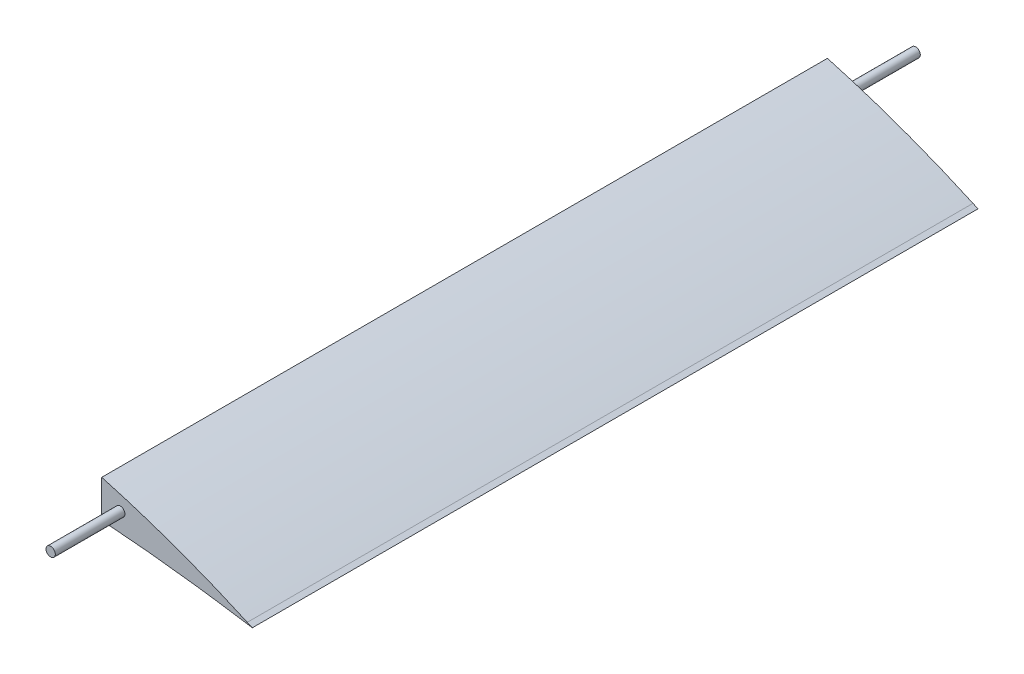
SolidWorks part; units mm, degrees
ref_plane "Front Plane" through (0, 0, 0) normal (0, 0, 1) x (1, 0, 0)
ref_plane "Top Plane" through (0, 0, 0) normal (0, 1, 0) x (1, 0, 0)
ref_plane "Right Plane" through (0, 0, 0) normal (1, 0, 0) x (0, 0, -1)
curve "Curve1"
  spline degree 3 poles (250.0905, 0.3018, 0) (249.9672, 0.3575, 0) (249.4747, 0.5802, 0) (248.3688, 1.0775, 0) (246.5311, 1.8956, 0) (243.97, 3.0187, 0) (240.6975, 4.4253, 0) (236.7287, 6.0881, 0) (232.0832, 7.9766, 0) (226.7833, 10.0544, 0) (220.8563, 12.2845, 0) (214.3322, 14.6254, 0) (207.2459, 17.0358, 0) (199.6354, 19.4726, 0) (191.5431, 21.8941, 0) (183.0146, 24.2576, 0) (174.0994, 26.5236, 0) (164.8497, 28.6528, 0) (155.3218, 30.6102, 0) (145.574, 32.3628, 0) (135.6679, 33.8811, 0) (125.6669, 35.1398, 0) (115.6368, 36.1207, 0) (105.5943, 36.804, 0) (95.5386, 37.2049, 0) (85.5334, 37.0417, 0) (75.7163, 36.3461, 0) (66.2328, 35.1462, 0) (57.1612, 33.4871, 0) (48.5745, 31.4248, 0) (40.5395, 29.0235, 0) (33.1158, 26.3532, 0) (26.3548, 23.4892, 0) (20.2996, 20.5079, 0) (14.9856, 17.4843, 0) (10.439, 14.4912, 0) (6.678, 11.5948, 0) (3.7114, 8.8542, 0) (1.5382, 6.3121, 0) (0.1509, 3.9928, 0) (-0.4561, 1.8641, 0) (-0.1455, -0.0657, 0) (1.0874, -1.5729, 0) (3.0441, -2.5516, 0) (5.6254, -3.1273, 0) (8.8498, -3.3551, 0) (12.7046, -3.2653, 0) (17.1664, -2.8882, 0) (22.2028, -2.2588, 0) (27.778, -1.4179, 0) (33.8542, -0.4079, 0) (40.3935, 0.7222, 0) (47.3585, 1.9245, 0) (54.7128, 3.1486, 0) (62.4221, 4.3431, 0) (70.4528, 5.4592, 0) (78.7727, 6.4469, 0) (87.3496, 7.2603, 0) (96.2165, 7.8657, 0) (105.3847, 8.1961, 0) (114.7995, 8.4827, 0) (124.348, 8.6738, 0) (133.9251, 8.7623, 0) (143.476, 8.7363, 0) (152.944, 8.5908, 0) (162.2721, 8.3266, 0) (171.4027, 7.9474, 0) (180.2781, 7.4625, 0) (188.8414, 6.8852, 0) (197.0363, 6.2309, 0) (204.8083, 5.5194, 0) (212.1048, 4.7711, 0) (218.8756, 4.0084, 0) (225.0732, 3.2526, 0) (230.6536, 2.5267, 0) (235.5766, 1.8504, 0) (239.8062, 1.2436, 0) (243.3111, 0.7223, 0) (246.0651, 0.3016, 0) (248.0475, -0.007, 0) (249.243, -0.1956, 0) (249.776, -0.2805, 0) (249.9095, -0.3018, 0) knots 0 0 0 0 0.00078 0.003116 0.006991 0.012379 0.01924 0.027529 0.037189 0.048153 0.06035 0.0737 0.088116 0.103505 0.119772 0.136815 0.154529 0.172806 0.191536 0.210607 0.229904 0.249313 0.268718 0.288003 0.307345 0.326725 0.345665 0.364063 0.381812 0.398811 0.414954 0.430141 0.444276 0.457267 0.469034 0.479505 0.488628 0.496375 0.502755 0.507847 0.511864 0.515267 0.518668 0.522659 0.527659 0.533842 0.541252 0.549872 0.559649 0.570512 0.582379 0.595163 0.608775 0.623132 0.63815 0.653755 0.669877 0.686453 0.703425 0.721111 0.739346 0.757734 0.776176 0.794567 0.812801 0.830771 0.84837 0.865489 0.88202 0.897855 0.912888 0.927018 0.940145 0.952174 0.963016 0.972591 0.980825 0.987653 0.993022 0.996888 0.999221 1 1 1 1
sketch "Sketch1" plane through (0, 0, 0) normal (0, 0, 1) x (1, 0, 0)
  line L0 (250.0905, 0.3018) -> (252.2491, -0.6745)
  line L2 (187.4095, 23.0316) -> (187.4095, 6.9716)
  line L5 (249.9095, -0.3018) -> (252.2491, -0.6745)
  spline S0 degree 3 poles (2456.644, 4483.8801) (345.0905, -56.1566) (299.6173, -21.964) (248.3688, 1.0775) (246.5311, 1.8956) (243.97, 3.0187) (240.6975, 4.4253) (236.7287, 6.0881) (232.0832, 7.9766) (226.7833, 10.0544) (220.8563, 12.2845) (214.3322, 14.6254) (207.2459, 17.0358) (199.6354, 19.4726) (191.5431, 21.8941) (183.0146, 24.2576) (174.0994, 26.5236) (164.8497, 28.6528) (155.3218, 30.6102) (145.574, 32.3628) (135.6679, 33.8811) (125.6669, 35.1398) (115.6368, 36.1207) (105.5943, 36.804) (95.5386, 37.2049) (85.5334, 37.0417) (75.7163, 36.3461) (66.2328, 35.1462) (57.1612, 33.4871) (48.5745, 31.4248) (40.5395, 29.0235) (33.1158, 26.3532) (26.3548, 23.4892) (20.2996, 20.5079) (14.9856, 17.4843) (10.439, 14.4912) (6.678, 11.5948) (3.7114, 8.8542) (1.5382, 6.3121) (0.1509, 3.9928) (-0.4561, 1.8641) (-0.1455, -0.0657) (1.0874, -1.5729) (3.0441, -2.5516) (5.6254, -3.1273) (8.8498, -3.3551) (12.7046, -3.2653) (17.1664, -2.8882) (22.2028, -2.2588) (27.778, -1.4179) (33.8542, -0.4079) (40.3935, 0.7222) (47.3585, 1.9245) (54.7128, 3.1486) (62.4221, 4.3431) (70.4528, 5.4592) (78.7727, 6.4469) (87.3496, 7.2603) (96.2165, 7.8657) (105.3847, 8.1961) (114.7995, 8.4827) (124.348, 8.6738) (133.9251, 8.7623) (143.476, 8.7363) (152.944, 8.5908) (162.2721, 8.3266) (171.4027, 7.9474) (180.2781, 7.4625) (188.8414, 6.8852) (197.0363, 6.2309) (204.8083, 5.5194) (212.1048, 4.7711) (218.8756, 4.0084) (225.0732, 3.2526) (230.6536, 2.5267) (235.5766, 1.8504) (239.8062, 1.2436) (243.3111, 0.7223) (246.0651, 0.3016) (248.0475, -0.007) (310.4513, -9.8504) (370.4532, -30.5336) (1217.1202, 4900.8972) knots -0.316987 -0.316987 -0.316987 -0.316987 0.00078 0.003116 0.006991 0.012379 0.01924 0.027529 0.037189 0.048153 0.06035 0.0737 0.088116 0.103505 0.119772 0.136815 0.154529 0.172806 0.191536 0.210607 0.229904 0.249313 0.268718 0.288003 0.307345 0.326725 0.345665 0.364063 0.381812 0.398811 0.414954 0.430141 0.444276 0.457267 0.469034 0.479505 0.488628 0.496375 0.502755 0.507847 0.511864 0.515267 0.518668 0.522659 0.527659 0.533842 0.541252 0.549872 0.559649 0.570512 0.582379 0.595163 0.608775 0.623132 0.63815 0.653755 0.669877 0.686453 0.703425 0.721111 0.739346 0.757734 0.776176 0.794567 0.812801 0.830771 0.84837 0.865489 0.88202 0.897855 0.912888 0.927018 0.940145 0.952174 0.963016 0.972591 0.980825 0.987653 0.993022 0.996888 0.999221 1.357276 1.357276 1.357276 1.357276 only from (250.0905, 0.3018) to (249.9095, -0.3018) construction
  spline S1 degree 3 poles (250.0905, 0.3018) (249.9672, 0.3575) (249.4747, 0.5802) (248.3688, 1.0775) (246.5311, 1.8956) (243.97, 3.0187) (240.6975, 4.4253) (236.7287, 6.0881) (232.0832, 7.9766) (226.7833, 10.0544) (220.8563, 12.2845) (214.3322, 14.6254) (207.2459, 17.0358) (199.6354, 19.4726) (192.963, 21.4692) (188.8298, 22.638) (187.4095, 23.0316) knots 0 0 0 0 0.00078 0.003116 0.006991 0.012379 0.01924 0.027529 0.037189 0.048153 0.06035 0.0737 0.088116 0.103505 0.119772 0.12827 0.12827 0.12827 0.12827
  spline S2 degree 3 poles (187.4095, 6.9716) (187.9265, 6.9347) (191.1827, 6.6982) (197.0363, 6.2309) (204.8083, 5.5194) (212.1048, 4.7711) (218.8756, 4.0084) (225.0732, 3.2526) (230.6536, 2.5267) (235.5766, 1.8504) (239.8062, 1.2436) (243.3111, 0.7223) (246.0651, 0.3016) (248.0475, -0.007) (249.243, -0.1956) (249.776, -0.2805) (249.9095, -0.3018) knots 0.879031 0.879031 0.879031 0.879031 0.88202 0.897855 0.912888 0.927018 0.940145 0.952174 0.963016 0.972591 0.980825 0.987653 0.993022 0.996888 0.999221 1 1 1 1
  dimension "D1" = 187.4095
extrude "Boss-Extrude1" add sketch "Sketch1" along normal mid plane 312.5
sketch "Sketch2" plane through (0, 0, 156.25) normal (0, 0, 1) x (1, 0, 0)
  line L0 (187.4095, 23.0316) -> (187.4095, 6.9716) construction
  circle A0 centre (195.4095, 14.3255) radius 2
  point P6 (196.3521, -0.3853)
  point P11 (0, 0)
  dimension "D1" = 4
  dimension "D2" = 8
  dimension "D3" = 15
extrude "Boss-Extrude2" add sketch "Sketch2" along normal blind 30
mirror "Mirror1" about plane through (0, 0, 0) normal (0, 0, 1) of "Boss-Extrude2"
